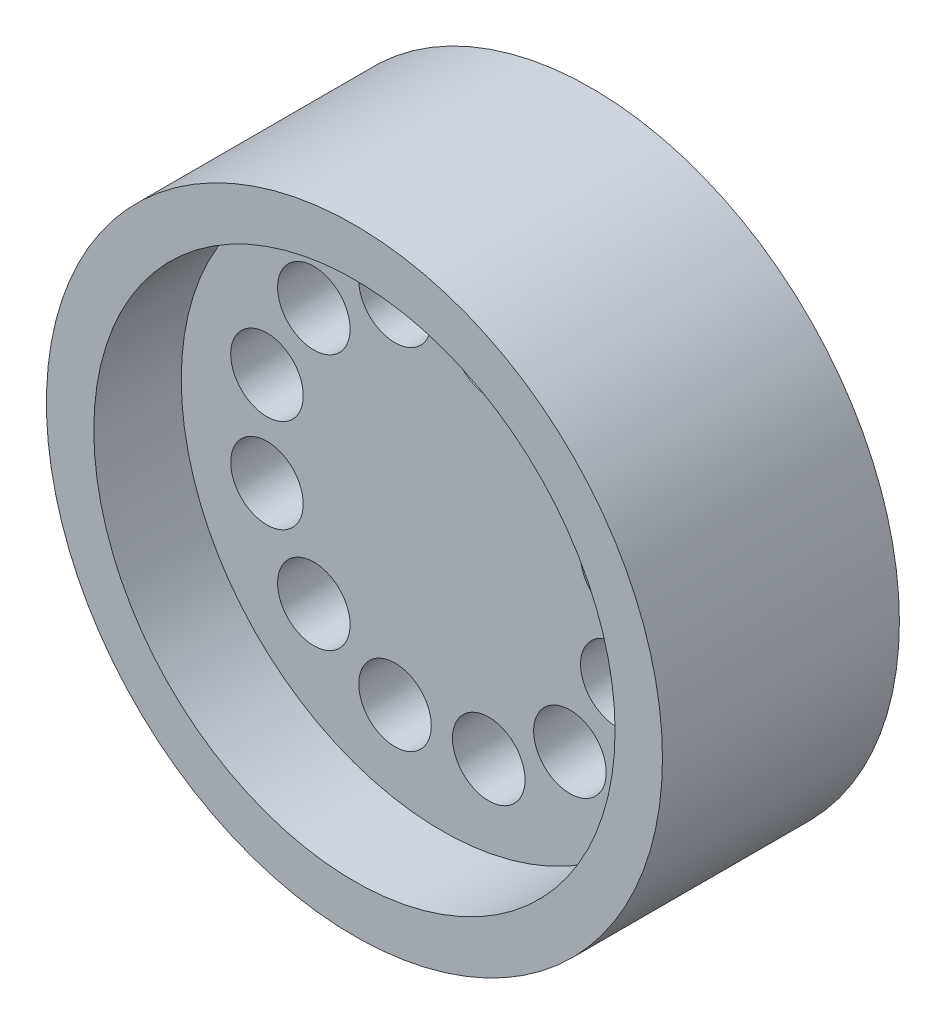
SolidWorks part; units mm, degrees
ref_plane "Front Plane" through (0, 0, 0) normal (0, 0, 1) x (1, 0, 0)
ref_plane "Top Plane" through (0, 0, 0) normal (0, 1, 0) x (1, 0, 0)
ref_plane "Right Plane" through (0, 0, 0) normal (1, 0, 0) x (0, 0, -1)
sketch "Sketch4" plane through (0, 0, 0) normal (1, 0, 0) x (0, 0, -1)
  line L0 (-14.433, -13.75) -> (17.0074, -13.75) construction
  line L1 (2.8866, -13.75) -> (-2.8866, -13.75)
  line L2 (2.8866, -13.75) -> (2.8866, 13.75)
  line L3 (2.8866, 13.75) -> (-2.8866, 13.75)
  line L4 (-2.8866, -13.75) -> (-2.8866, 13.75)
  line L5 (2.8866, -13.75) -> (-2.8866, 13.75) construction
  line L6 (2.8866, 13.75) -> (-2.8866, -13.75) construction
  line L7 (-12.1134, 13.75) -> (12.8866, 13.75)
  line L8 (-12.1134, 13.75) -> (-12.1134, 18.75)
  line L9 (-12.1134, 18.75) -> (12.8866, 18.75)
  line L10 (12.8866, 13.75) -> (12.8866, 18.75)
  point P0 (0, 0)
  dimension "D1" = 27.5
  dimension "D2" = 5
  dimension "D3" = 25
  dimension "D4" = 0
  dimension "D5" = 10
revolve "Revolve3" add sketch "Sketch4" angle 360 about L0
sketch "Sketch5" plane through (0, 0, -2.8866) normal (0, 0, -1) x (-1, 0, 0)
  line L0 (0, 13.75) -> (0, -41.25) construction
  line L1 (27.5, -13.75) -> (-27.5, -13.75) construction
  circle A2 centre (4.9452, 4.7058) radius 3.8272
  circle A3 centre (13.5106, -0.2394) radius 3.8272
  circle A4 centre (18.4558, -8.8048) radius 3.8272
  circle A5 centre (18.4558, -18.6952) radius 3.8272
  circle A6 centre (13.5106, -27.2606) radius 3.8272
  circle A7 centre (4.9452, -32.2058) radius 3.8272
  circle A8 centre (-4.9452, -32.2058) radius 3.8272
  circle A9 centre (-13.5106, -27.2606) radius 3.8272
  circle A10 centre (-18.4558, -18.6952) radius 3.8272
  circle A11 centre (-18.4558, -8.8048) radius 3.8272
  circle A12 centre (-13.5106, -0.2394) radius 3.8272
  circle A13 centre (-4.9452, 4.7058) radius 3.8272
  circle A14 centre (0, -13.75) radius 27.5 construction
extrude "Cut-Extrude1" cut sketch "Sketch5" against normal blind 10
sketch "Sketch7" plane through (0, 0, -2.8866) normal (0, 0, -1) x (-1, 0, 0)
  line L0 (0, 13.75) -> (0, -41.25) construction
  line L1 (-27.5, -13.75) -> (27.5, -13.75) construction
  circle A0 centre (0, -13.75) radius 27.5 construction
  circle A1 centre (0, -13.75) radius 2.5
  dimension "D1" = 5
extrude "Boss-Extrude1" add sketch "Sketch7" along normal blind 30
